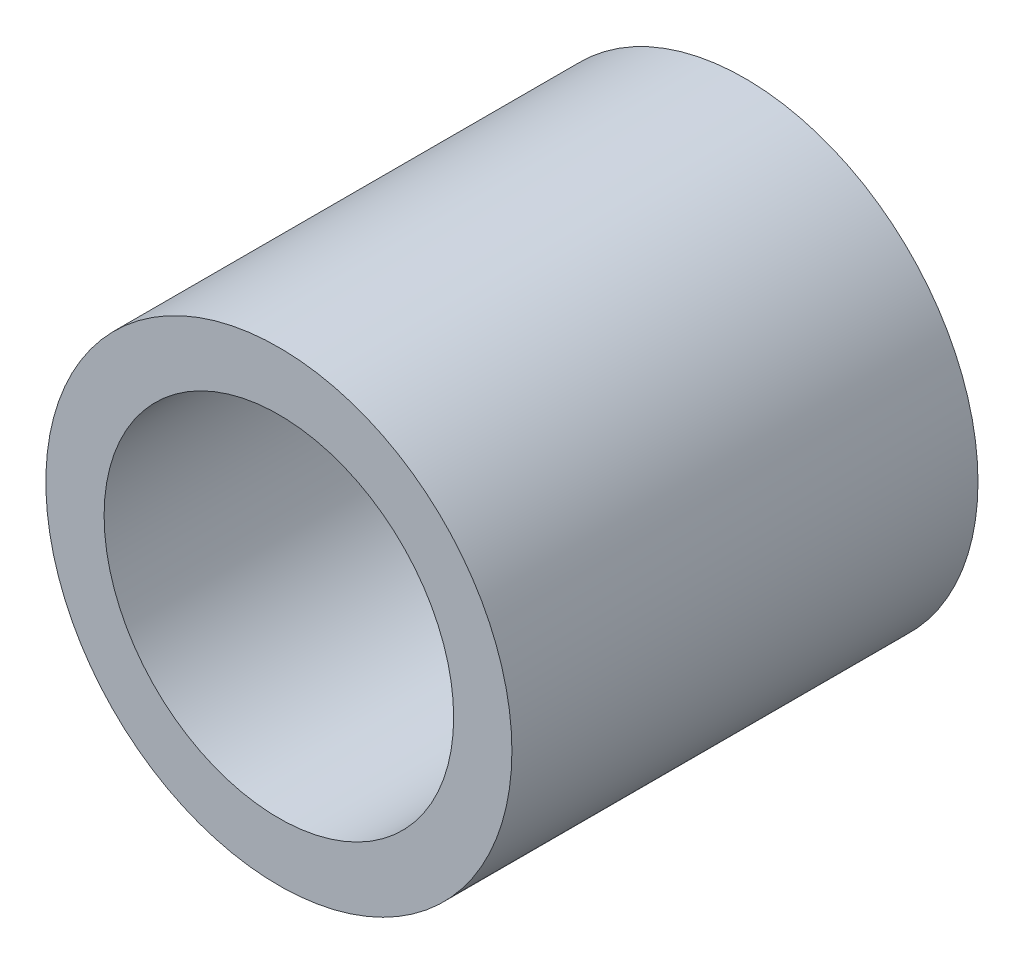
SolidWorks part; units mm, degrees
material "Tin Bearing Bronze"
ref_plane "Front Plane" through (0, 0, 0) normal (0, 0, 1) x (1, 0, 0)
ref_plane "Top Plane" through (0, 0, 0) normal (0, 1, 0) x (1, 0, 0)
ref_plane "Right Plane" through (0, 0, 0) normal (1, 0, 0) x (0, 0, -1)
sketch "Sketch2" plane through (0, 0, 0) normal (0, 0, 1) x (1, 0, 0)
  circle A0 centre (0, 0) radius 6.35
  circle A1 centre (0, 0) radius 4.7625
  dimension "D1" = 12.7
  dimension "D2" = 9.525
extrude "Boss-Extrude1" add sketch "Sketch2" along normal blind 12.7
